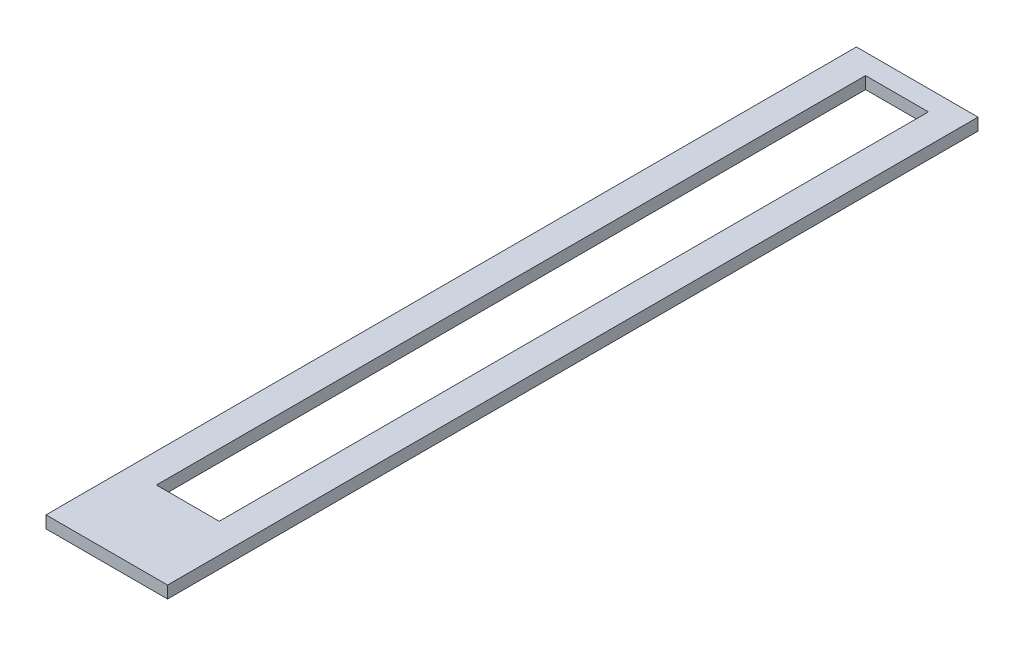
SolidWorks part; units mm, degrees
ref_plane "Plano frontal" through (0, 0, 0) normal (0, 0, 1) x (1, 0, 0)
ref_plane "Plano superior" through (0, 0, 0) normal (0, 1, 0) x (1, 0, 0)
ref_plane "Plano direito" through (0, 0, 0) normal (1, 0, 0) x (0, 0, -1)
sketch "Esboço1" plane through (0, 0, 0) normal (0, 1, 0) x (1, 0, 0)
  line L1 (-15, -100) -> (15, -100)
  line L2 (-15, -100) -> (-15, 100)
  line L3 (-15, 100) -> (15, 100)
  line L4 (15, -100) -> (15, 100)
  line L5 (-15, -100) -> (15, 100) construction
  line L6 (-15, 100) -> (15, -100) construction
  point P0 (0, 0)
  dimension "D1" = 30
  dimension "D2" = 200
extrude "Ressalto-extrusão1" add sketch "Esboço1" along normal blind 3
sketch "Esboço2" plane through (0, 3, 0) normal (0, 1, 0) x (1, 0, 0)
  line L0 (15, 100) -> (-15, 100) construction
  line L1 (-7.75, 95) -> (7.75, 95)
  line L2 (-7.75, 95) -> (-7.75, -80)
  line L3 (-7.75, -80) -> (7.75, -80)
  line L4 (7.75, 95) -> (7.75, -80)
  line L5 (-15, 100) -> (-15, -100) construction
  dimension "D1" = 5
  dimension "D2" = 15.5
  dimension "D3" = 7.25
  dimension "D4" = 175
extrude "Corte-extrusão1" cut sketch "Esboço2" against normal blind 5
